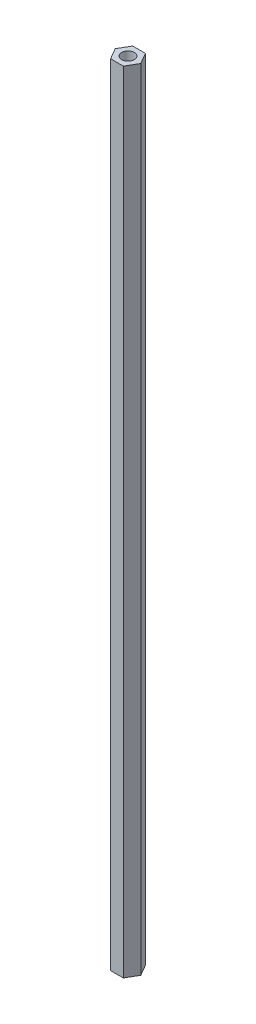
SolidWorks part; units mm, degrees
ref_plane "Front Plane" through (0, 0, 0) normal (0, 0, 1) x (1, 0, 0)
ref_plane "Top Plane" through (0, 0, 0) normal (0, 1, 0) x (1, 0, 0)
ref_plane "Right Plane" through (0, 0, 0) normal (1, 0, 0) x (0, 0, -1)
sketch "Sketch1" plane through (0, 0, 0) normal (0, 1, 0) x (1, 0, 0)
  line L1 (2.0207, 3.5) -> (-2.0207, 3.5)
  line L2 (-2.0207, 3.5) -> (-4.0415, 0)
  line L3 (-4.0415, 0) -> (-2.0207, -3.5)
  line L4 (-2.0207, -3.5) -> (2.0207, -3.5)
  line L5 (2.0207, -3.5) -> (4.0415, 0)
  line L6 (4.0415, 0) -> (2.0207, 3.5)
  circle A0 centre (0, 0) radius 3.5 construction
  circle A1 centre (0, 0) radius 2
  dimension "D1" = 4
  dimension "D2" = 7
extrude "Boss-Extrude1" add sketch "Sketch1" along normal blind 250
